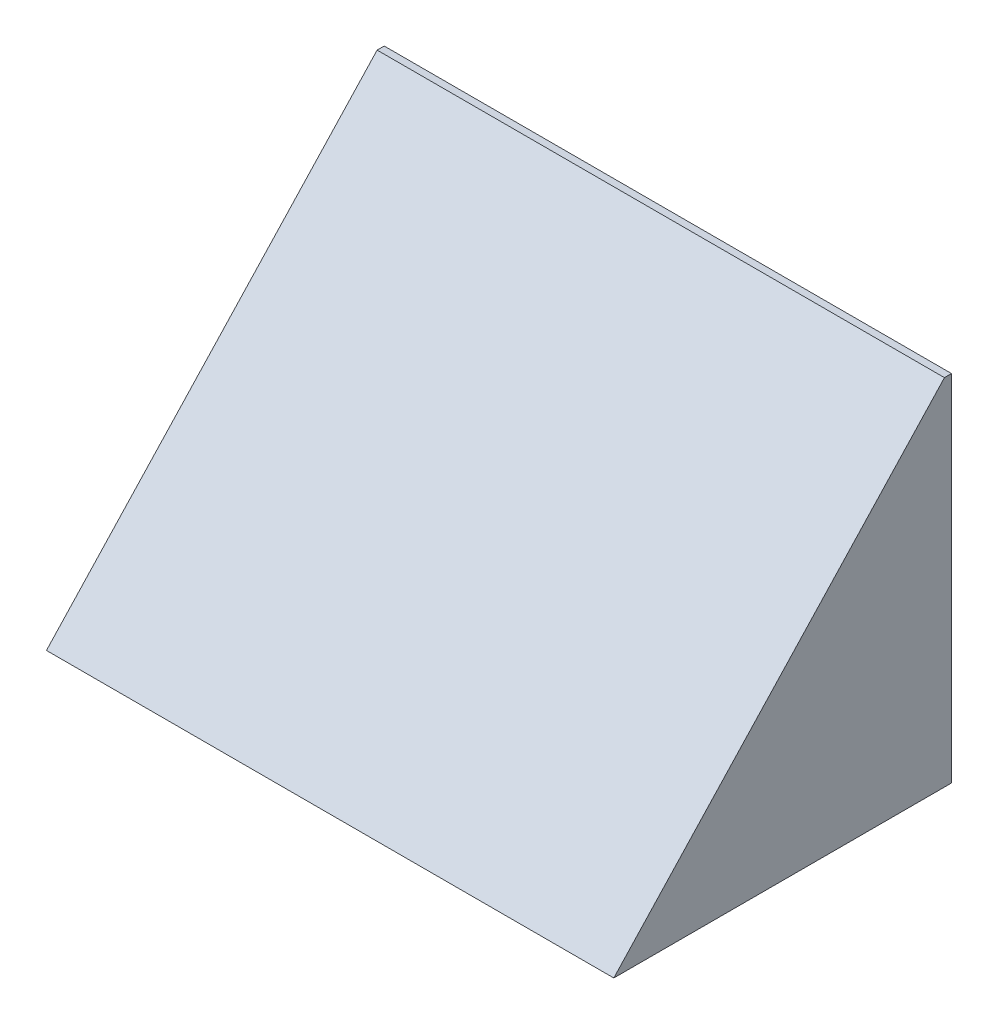
SolidWorks part; units mm, degrees
ref_plane "前视基准面" through (0, 0, 0) normal (0, 0, 1) x (1, 0, 0)
ref_plane "上视基准面" through (0, 0, 0) normal (0, 1, 0) x (1, 0, 0)
ref_plane "右视基准面" through (0, 0, 0) normal (1, 0, 0) x (0, 0, -1)
sketch "草图2" plane through (0, 0, 0) normal (0, 0, 1) x (1, 0, 0)
  line L1 (-40, 25) -> (40, 25)
  line L2 (-40, 25) -> (-40, -25)
  line L3 (-40, -25) -> (40, -25)
  line L4 (40, 25) -> (40, -25)
  line L5 (-40, 25) -> (40, -25) construction
  line L6 (-40, -25) -> (40, 25) construction
  point P0 (0, 0)
  dimension "D1" = 80
  dimension "D2" = 50
extrude "凸台-拉伸2" add sketch "草图2" along normal blind 1
draft "拔模6" type of draft neutral plane draft angle 43 faces to draft 1 face at (0, 0, 1) neutral plane through (-40, 25, 1) neutral plane normal (0, 1, 0) parameters "D1"=43
